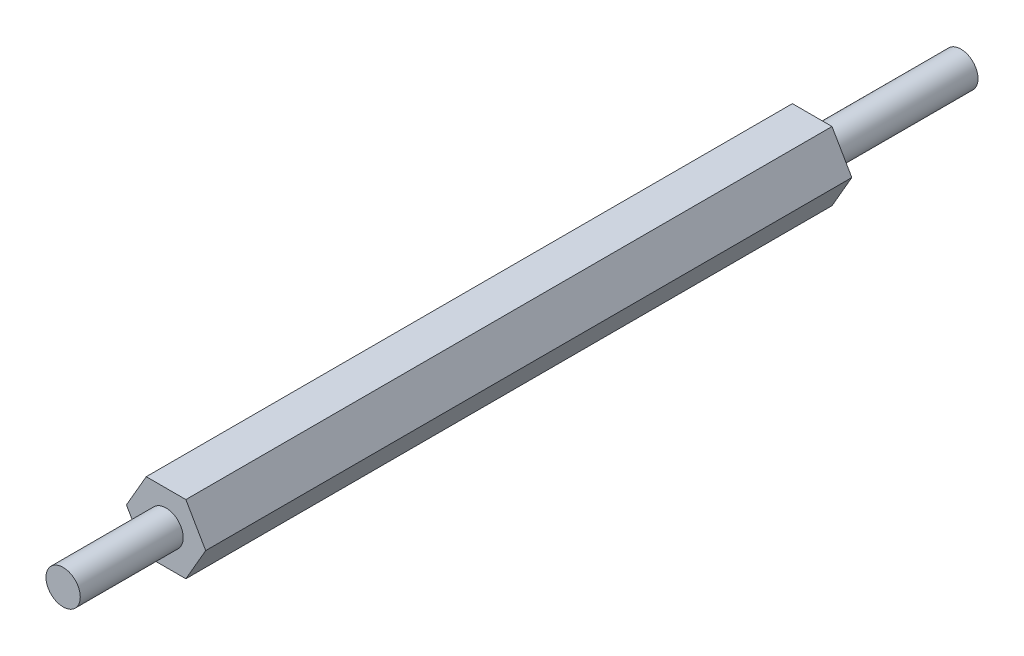
SolidWorks part; units mm, degrees
material "黄铜"
ref_plane "前视基准面" through (0, 0, 0) normal (0, 0, 1) x (1, 0, 0)
ref_plane "上视基准面" through (0, 0, 0) normal (0, 1, 0) x (1, 0, 0)
ref_plane "右视基准面" through (0, 0, 0) normal (1, 0, 0) x (0, 0, -1)
sketch "草图1" plane through (0, 0, 0) normal (0, 0, 1) x (1, 0, 0)
  line L1 (3.4641, 0) -> (1.7321, 3)
  line L2 (1.7321, 3) -> (-1.7321, 3)
  line L3 (-1.7321, 3) -> (-3.4641, 0)
  line L4 (-3.4641, 0) -> (-1.7321, -3)
  line L5 (-1.7321, -3) -> (1.7321, -3)
  line L6 (1.7321, -3) -> (3.4641, 0)
  circle A0 centre (0, 0) radius 3 construction
  dimension "D1" = 6
extrude "六角柱_有效长56.5" add sketch "草图1" along normal blind 56.5
sketch "草图2" plane through (0, 0, 0) normal (0, 0, 1) x (1, 0, 0)
  circle A0 centre (0, 0) radius 1.5
  dimension "D1" = 3
extrude "下端M3公头_长13" add sketch "草图2" along normal blind 13 from offset 13
sketch "草图3" plane through (0, 0, 0) normal (0, 0, 1) x (1, 0, 0)
  circle A0 centre (0, 0) radius 1.5
  dimension "D1" = 3
extrude "上端M3公头_长9" add sketch "草图3" along normal blind 9 from offset 56.5
